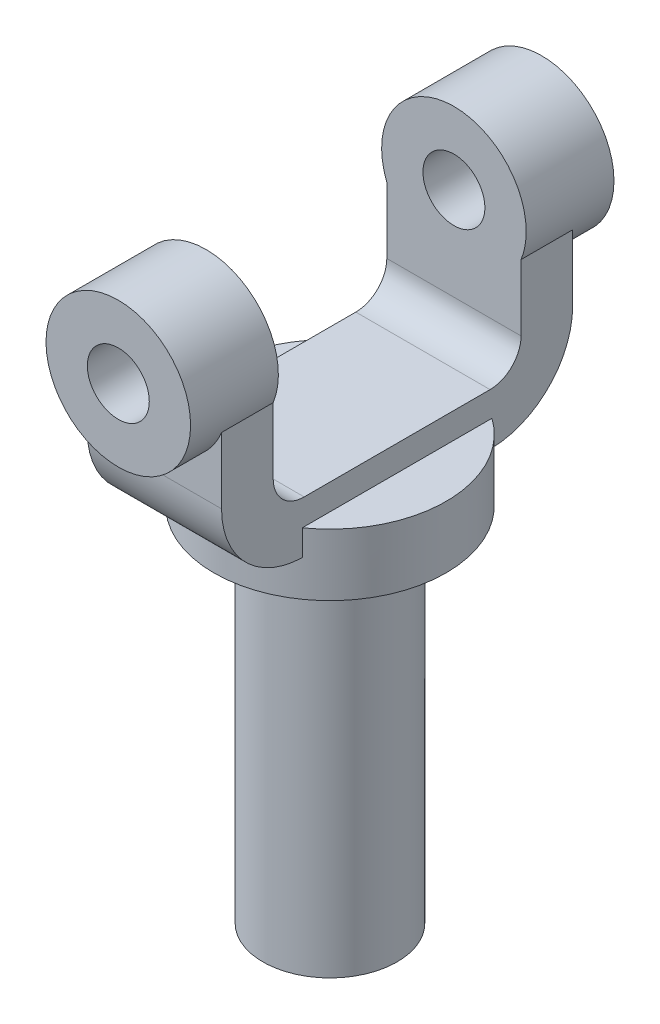
SolidWorks part; units mm, degrees
ref_plane "Front Plane" through (0, 0, 0) normal (0, 0, 1) x (1, 0, 0)
ref_plane "Top Plane" through (0, 0, 0) normal (0, 1, 0) x (1, 0, 0)
ref_plane "Right Plane" through (0, 0, 0) normal (1, 0, 0) x (0, 0, -1)
sketch "Sketch1" plane through (0, 0, 0) normal (0, 0, 1) x (1, 0, 0)
  line L0 (0, 0) -> (22.5, 0)
  line L1 (22.5, 0) -> (22.5, -12)
  line L2 (22.5, -12) -> (13, -12)
  line L3 (13, -12) -> (13, -82)
  line L4 (13, -82) -> (0, -82)
  line L5 (0, -82) -> (0, 0)
  line L6 (0, 0) -> (0, 104.9332) construction
  dimension "D1" = 12
  dimension "D2" = 26
  dimension "D3" = 82
  dimension "D4" = 45
revolve "Revolve1" add sketch "Sketch1" angle 360 about L6
sketch "Sketch2" plane through (0, 0, 0) normal (1, 0, 0) x (0, 0, -1)
  line L0 (0, 0) -> (0, 42.2359) construction
  line L1 (-18, 5) -> (18, 5)
  line L2 (-18, -5) -> (18, -5)
  line L3 (24, 11) -> (24, 29)
  line L4 (24, 29) -> (34, 29)
  line L5 (34, 29) -> (34, 11)
  line L7 (-34, 29) -> (-34, 11)
  line L8 (-24, 29) -> (-34, 29)
  line L9 (-24, 11) -> (-24, 29)
  arc A0 (18, 5) -> (24, 11) centre (18, 11) ccw
  arc A1 (18, -5) -> (34, 11) centre (18, 11) ccw
  arc A2 (-18, -5) -> (-34, 11) centre (-18, 11) cw
  arc A3 (-18, 5) -> (-24, 11) centre (-18, 11) cw
  point P11 (0, 0)
  point P21 (0, 0)
  point P22 (0, 0)
  point P23 (0, 0)
  point P24 (-24, 29)
  dimension "D2" = 16
  dimension "D3" = 6
  dimension "D4" = 34
  dimension "D5" = 68
  dimension "D6" = 10
extrude "Boss-Extrude1" add sketch "Sketch2" along normal mid plane 26 contours L9 L8 L7 A2 L2 A1 L5 L4 L3 A0 L1 A3
sketch "Sketch3" plane through (0, 0, -24) normal (0, 0, 1) x (1, 0, 0)
  circle A0 centre (0, 29.0041) radius 14
  circle A1 centre (0, 29.0041) radius 6
  point P3 (0, 0)
  dimension "D1" = 28
  dimension "D2" = 12
  dimension "D3" = 34
  dimension "D4" = 29.0041
extrude "Boss-Extrude2" add sketch "Sketch3" against normal blind 17
mirror "Mirror1" about plane through (0, 0, 0) normal (0, 0, 1) of "Boss-Extrude2"
sketch "Sketch4" plane through (0, 0, -34) normal (0, 0, -1) x (-1, 0, 0)
  circle A0 centre (0, 29.0041) radius 6
extrude "Cut-Extrude1" cut sketch "Sketch4" against normal through all both and the other way through all
fillet "Fillet1" radius 2 1 edges at (0, -12, -13)
